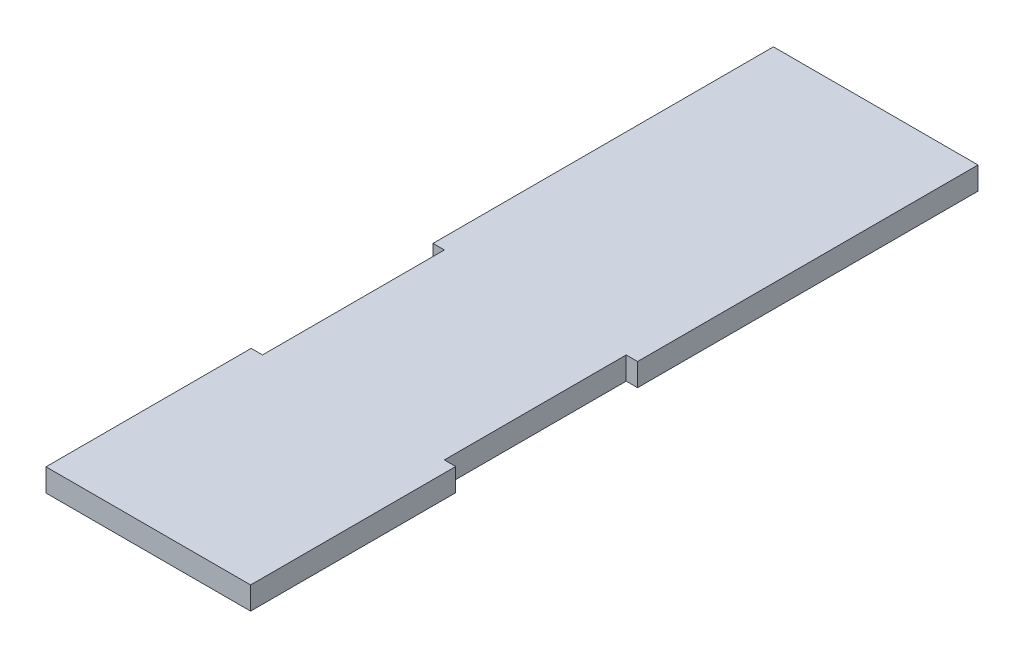
SolidWorks part; units mm, degrees
material "AISI 4130 Steel, annealed at 865C"
ref_plane "X-Y Datum" through (0, 0, 0) normal (0, 0, 1) x (1, 0, 0)
ref_plane "X-Z Datum" through (0, 0, 0) normal (0, 1, 0) x (1, 0, 0)
ref_plane "Y-Z Datum" through (0, 0, 0) normal (1, 0, 0) x (0, 0, -1)
sketch "Sketch1" plane through (0, 0, 0) normal (0, 1, 0) x (1, 0, 0)
  line L0 (-7.1437, -25.4) -> (-7.1437, -11.0744) construction
  line L1 (-7.1437, -25.4) -> (7.1438, -25.4)
  line L2 (-7.1437, -25.4) -> (-7.1437, 25.4)
  line L3 (-7.1437, 25.4) -> (7.1438, 25.4)
  line L4 (7.1438, -25.4) -> (7.1438, 25.4)
  line L5 (-7.1437, -25.4) -> (7.1438, 25.4) construction
  line L6 (-7.1437, 25.4) -> (7.1438, -25.4) construction
  line L7 (0, -43.0151) -> (0, 43.0151) construction
  line L8 (-7.1437, -11.0744) -> (-6.35, -11.0744)
  line L9 (-7.1437, -11.0744) -> (-7.1437, 1.6256)
  line L10 (-7.1437, 1.6256) -> (-6.35, 1.6256)
  line L11 (-6.35, -11.0744) -> (-6.35, 1.6256)
  line L12 (7.1437, -11.0744) -> (6.35, -11.0744)
  line L13 (6.35, -11.0744) -> (6.35, 1.6256)
  line L14 (7.1437, 1.6256) -> (6.35, 1.6256)
  point P1 (0, 0)
  dimension "D1" = 50.8
  dimension "D2" = 14.2875
  dimension "D3" = 14.3256
  dimension "D4" = 0.7937
  dimension "D5" = 12.7
extrude "Boss-Extrude1" add sketch "Sketch1" along normal blind 1.5875 contours L14 L4 L3 L2 L10 L11 L8 L1 L12 L13
